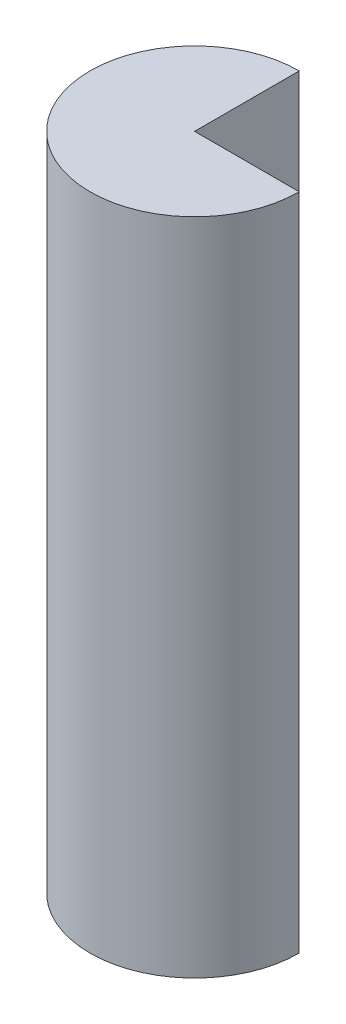
SolidWorks part; units mm, degrees
ref_plane "Front Plane" through (0, 0, 0) normal (0, 0, 1) x (1, 0, 0)
ref_plane "Top Plane" through (0, 0, 0) normal (0, 1, 0) x (1, 0, 0)
ref_plane "Right Plane" through (0, 0, 0) normal (1, 0, 0) x (0, 0, -1)
sketch "Sketch1" plane through (0, 0, 0) normal (0, 1, 0) x (1, 0, 0)
  line L0 (0, 0) -> (0, 12.7)
  line L1 (0, 0) -> (12.7, 0)
  arc A0 (0, 12.7) -> (12.7, 0) centre (0, 0) ccw
  dimension "D1" = 25.4
extrude "Boss-Extrude1" add sketch "Sketch1" along normal blind 80
